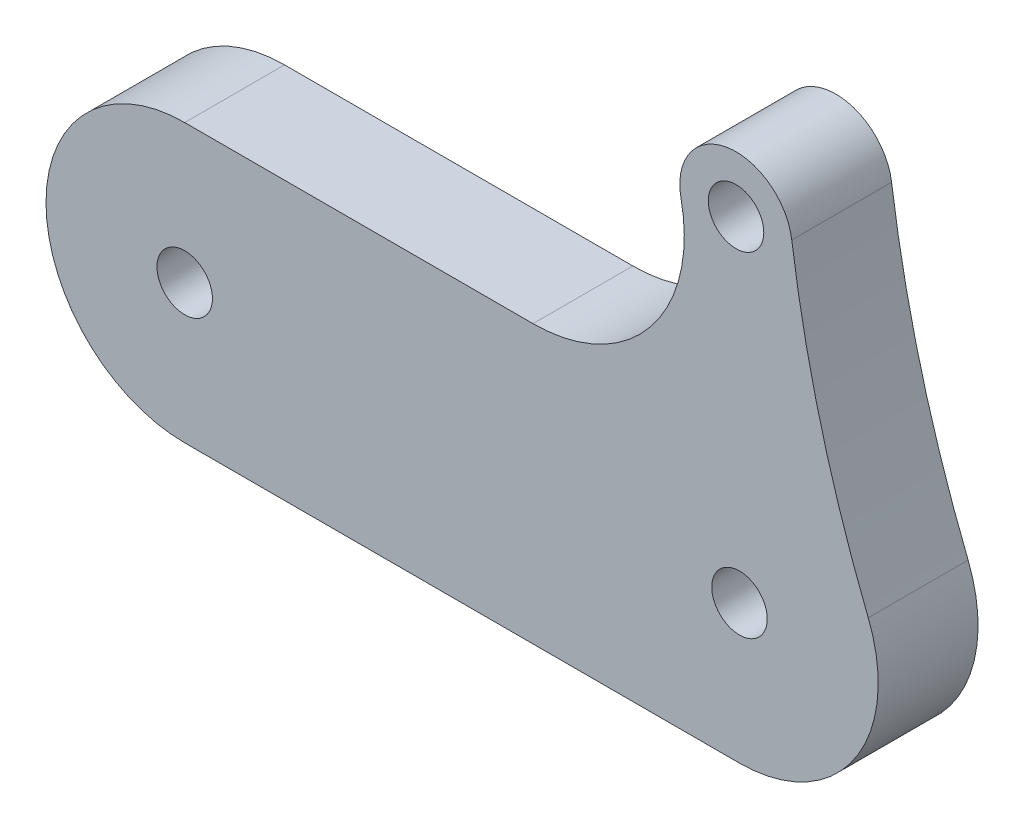
SolidWorks part; units mm, degrees
ref_plane "Front Plane" through (0, 0, 0) normal (0, 0, 1) x (1, 0, 0)
ref_plane "Top Plane" through (0, 0, 0) normal (0, 1, 0) x (1, 0, 0)
ref_plane "Right Plane" through (0, 0, 0) normal (1, 0, 0) x (0, 0, -1)
sketch "Sketch1" plane through (0, 0, 0) normal (0, 0, 1) x (1, 0, 0)
  line L0 (0, 0) -> (20, 0) construction
  line L1 (0, 5) -> (12.5569, 5)
  line L2 (0, -5) -> (20, -5)
  arc A0 (0, 5) -> (0, -5) centre (0, 0) ccw
  arc A1 (20, -5) -> (24.6411, 1.8601) centre (20, 0) ccw
  circle A2 centre (0, 0) radius 1
  circle A3 centre (20, 0) radius 1
  circle A4 centre (19.8752, 12) radius 1
  arc A5 (21.8836, 12.2758) -> (17.8919, 11.5807) centre (19.8752, 12) ccw
  arc A6 (12.5569, 5) -> (17.8919, 11.5807) centre (12.5569, 10.4529) ccw
  arc A7 (21.8836, 12.2758) -> (24.6411, 1.8601) centre (65.6101, 18.2795) ccw
  point P3 (10, 0)
  dimension "D3" = 2
  dimension "D7" = 5
  dimension "D2" = 5
  dimension "D5" = 5
  dimension "D1" = 20
  dimension "D4" = 12
  dimension "D6" = 20
  dimension "D8" = 12.5569
  dimension "D11" = 12
extrude "Boss-Extrude1" add sketch "Sketch1" along normal blind 3.6
